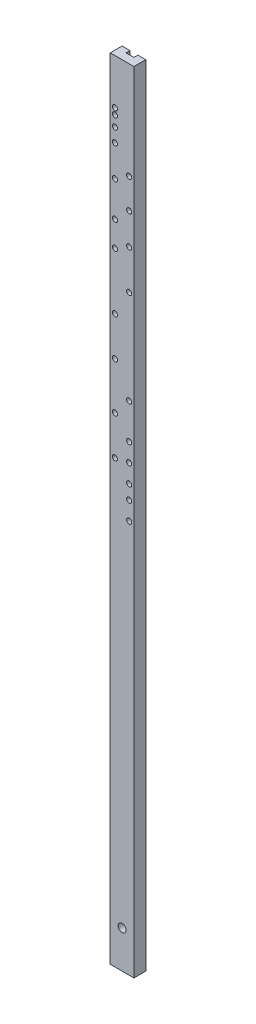
SolidWorks part; units mm, degrees
ref_plane "Front Plane" through (0, 0, 0) normal (0, 0, 1) x (1, 0, 0)
ref_plane "Top Plane" through (0, 0, 0) normal (0, 1, 0) x (1, 0, 0)
ref_plane "Right Plane" through (0, 0, 0) normal (1, 0, 0) x (0, 0, -1)
sketch "Sketch1" plane through (0, 0, 0) normal (1, 0, 0) x (0, 0, -1)
  line L1 (9.525, 635) -> (-9.525, 635)
  line L2 (9.525, 635) -> (9.525, -635)
  line L3 (9.525, -635) -> (-9.525, -635)
  line L4 (-9.525, 635) -> (-9.525, -635)
  line L5 (9.525, 635) -> (-9.525, -635) construction
  line L6 (9.525, -635) -> (-9.525, 635) construction
  point P0 (0, 0)
  dimension "D1" = 1270
  dimension "D2" = 19.05
extrude "Boss-Extrude1" add sketch "Sketch1" along normal mid plane 38.1
sketch "Sketch2" plane through (0, 0, 9.525) normal (0, 0, 1) x (1, 0, 0)
  line L0 (19.05, -635) -> (-19.05, -635) construction
  line L1 (0, -574.675) -> (0, -635) construction
  circle A0 centre (0, -574.675) radius 6.35
  dimension "D2" = 12.7
  dimension "D1" = 60.325
extrude "Cut-Extrude1" cut sketch "Sketch2" against normal through all
sketch "Sketch3" plane through (0, 0, 0) normal (1, 0, 0) x (0, 0, -1)
  line L0 (-41.275, -57.2492) -> (-50.8, -514.35)
  line L2 (-9.525, -635) -> (9.525, -635) construction
  line L3 (-52.3436, -234.8572) -> (-128.9079, -233.2617) construction
  line L4 (-44.159, -195.6492) -> (-58.8878, -195.3423)
  line L5 (-44.159, -195.6492) -> (-45.7994, -274.3721)
  line L6 (-45.7994, -274.3721) -> (-60.5282, -274.0652)
  line L7 (-58.8878, -195.3423) -> (-60.5282, -274.0652)
  line L8 (-44.159, -195.6492) -> (-60.5282, -274.0652) construction
  line L9 (-45.7994, -274.3721) -> (-58.8878, -195.3423) construction
  line L10 (-198.2402, -238.1684) -> (-59.8403, -241.0523)
  line L11 (-198.2402, -238.1684) -> (-197.9756, -225.4711)
  line L12 (-197.9756, -225.4711) -> (-59.5757, -228.3551)
  line L13 (-59.8403, -241.0523) -> (-59.5757, -228.3551)
  line L14 (-198.2402, -238.1684) -> (-59.5757, -228.3551) construction
  line L15 (-197.9756, -225.4711) -> (-59.8403, -241.0523) construction
  line L16 (-9.525, 635) -> (-9.525, -635) construction
  circle A0 centre (-46.0375, -285.7996) radius 228.6
  point P12 (-52.3436, -234.8572)
  point P13 (-128.9079, -233.2617)
  point P20 (-41.275, -501.65)
  point P21 (-41.275, -501.65)
  point P22 (-41.275, -501.65)
  point P23 (-66.8005, -501.65)
  point P24 (-65.2544, -229.6792)
  point P25 (-67.2565, -501.65)
  dimension "D1" = 457.2
  dimension "D2" = 31.75
  dimension "D3" = 120.65
  dimension "D4" = 12.7
  dimension "D5" = 138.43
  dimension "D6" = 78.74
  dimension "D7" = 14.732
  dimension "D8" = 41.275
  dimension "D9" = 177.8
ref_plane "Plane1" through (0, -235.8455, 4.9145) normal (0, 0.9998, -0.0208) x (0, 0.0208, 0.9998)
sketch "Sketch7" plane through (0, -235.8455, 4.9145) normal (0, 0.9998, -0.0208) x (0, 0.0208, 0.9998)
  line L0 (193.2353, 0) -> (54.8053, 0) construction
  line L1 (217.5832, 38.1) -> (55.0735, 38.1)
  line L2 (217.5832, 38.1) -> (217.5832, -38.1)
  line L3 (217.5832, -38.1) -> (55.0735, -38.1)
  line L4 (55.0735, 38.1) -> (55.0735, -38.1)
  line L5 (217.5832, 38.1) -> (55.0735, -38.1) construction
  line L6 (217.5832, -38.1) -> (55.0735, 38.1) construction
  point P0 (136.3283, 0)
  point P7 (55.2318, 38.1)
  point P8 (0, 0)
  point P9 (64.2735, -38.1)
  point P10 (0, 0)
  dimension "D1" = 76.2
sketch "Sketch4" plane through (0, 635, 0) normal (0, 1, 0) x (1, 0, 0)
  line L0 (19.05, 9.525) -> (-19.05, 9.525) construction
  line L1 (-6.35, 15.875) -> (6.35, 15.875)
  line L2 (-6.35, 15.875) -> (-6.35, 3.175)
  line L3 (-6.35, 3.175) -> (6.35, 3.175)
  line L4 (6.35, 15.875) -> (6.35, 3.175)
  line L5 (-6.35, 15.875) -> (6.35, 3.175) construction
  line L6 (-6.35, 3.175) -> (6.35, 15.875) construction
  point P0 (0, 9.525)
  dimension "D1" = 12.7
  dimension "D2" = 6.35
extrude "Cut-Extrude2" cut sketch "Sketch4" against normal through all
sketch "Sketch5" plane through (0, 0, 9.525) normal (0, 0, 1) x (1, 0, 0)
  line L0 (-11.43, 635) -> (-11.43, -635) construction
  line L1 (19.05, 635) -> (-19.05, 635) construction
  line L2 (19.05, -635) -> (-19.05, -635) construction
  line L3 (-11.43, -635) -> (11.43, -635) construction
  line L4 (11.43, -635) -> (11.43, 635) construction
  line L5 (11.43, 635) -> (-11.43, 635) construction
  line L8 (-11.43, 0) -> (0, 0) construction
  line L9 (0, 0) -> (11.43, 0) construction
  circle A0 centre (-11.43, 513.3021) radius 1.905
  circle A1 centre (11.43, 478.2636) radius 1.905
  circle A2 centre (-11.43, 463.3456) radius 1.905
  circle A3 centre (11.43, 430.1139) radius 1.905
  circle A4 centre (-11.43, 407.0641) radius 1.905
  circle A5 centre (11.43, 379.8427) radius 1.905
  circle A6 centre (-11.43, 366.5515) radius 1.905
  circle A7 centre (11.43, 316.419) radius 1.905
  circle A8 centre (-11.43, 535.4221) radius 1.905
  circle A9 centre (-11.43, 552.285) radius 1.905
  circle A10 centre (-11.43, 562.4307) radius 1.905
  circle A11 centre (11.43, 165.1498) radius 1.905
  circle A12 centre (11.43, 108.4563) radius 1.905
  circle A13 centre (11.43, 79.0585) radius 1.905
  circle A14 centre (11.43, 49.6539) radius 1.905
  circle A15 centre (11.43, 27.0432) radius 1.905
  circle A16 centre (11.43, -2.1989) radius 1.905
  circle A17 centre (-11.43, 74.3869) radius 1.905
  circle A18 centre (-11.43, 137.0132) radius 1.905
  circle A19 centre (-11.43, 212.5967) radius 1.905
  circle A20 centre (-11.43, 275.1797) radius 1.905
  dimension "D3" = 3.81
  dimension "D1" = 22.86
extrude "Cut-Extrude3" cut sketch "Sketch5" against normal through all
sketch "Sketch6" plane through (0, 0, 9.525) normal (0, 0, 1) x (1, 0, 0)
  circle A0 centre (-11.43, 513.3021) radius 4.1275
  circle A1 centre (11.43, 478.2636) radius 4.1275
  circle A2 centre (-11.43, 463.3456) radius 4.1275
  circle A3 centre (11.43, 430.1139) radius 4.1275
  circle A4 centre (11.43, 379.8427) radius 4.1275
  circle A5 centre (11.43, 316.419) radius 4.1275
  circle A6 centre (-11.43, 366.5515) radius 4.1275
  circle A7 centre (-11.43, 407.0641) radius 4.1275
  circle A8 centre (-11.43, 562.4307) radius 4.1275
  circle A9 centre (-11.43, 552.285) radius 4.1275
  circle A10 centre (-11.43, 535.4221) radius 4.1275
  circle A11 centre (-11.43, 275.1797) radius 4.1275
  circle A12 centre (-11.43, 212.5967) radius 4.1275
  circle A13 centre (11.43, 165.1498) radius 4.1275
  circle A14 centre (-11.43, 137.0132) radius 4.1275
  circle A15 centre (11.43, 108.4563) radius 4.1275
  circle A16 centre (11.43, 79.0585) radius 4.1275
  circle A17 centre (-11.43, 74.3869) radius 4.1275
  circle A18 centre (11.43, 49.6539) radius 4.1275
  circle A19 centre (11.43, 27.0432) radius 4.1275
  circle A20 centre (11.43, -2.1989) radius 4.1275
  dimension "D1" = 8.255
extrude "Cut-Extrude4" cut sketch "Sketch6" against normal blind 7.747
